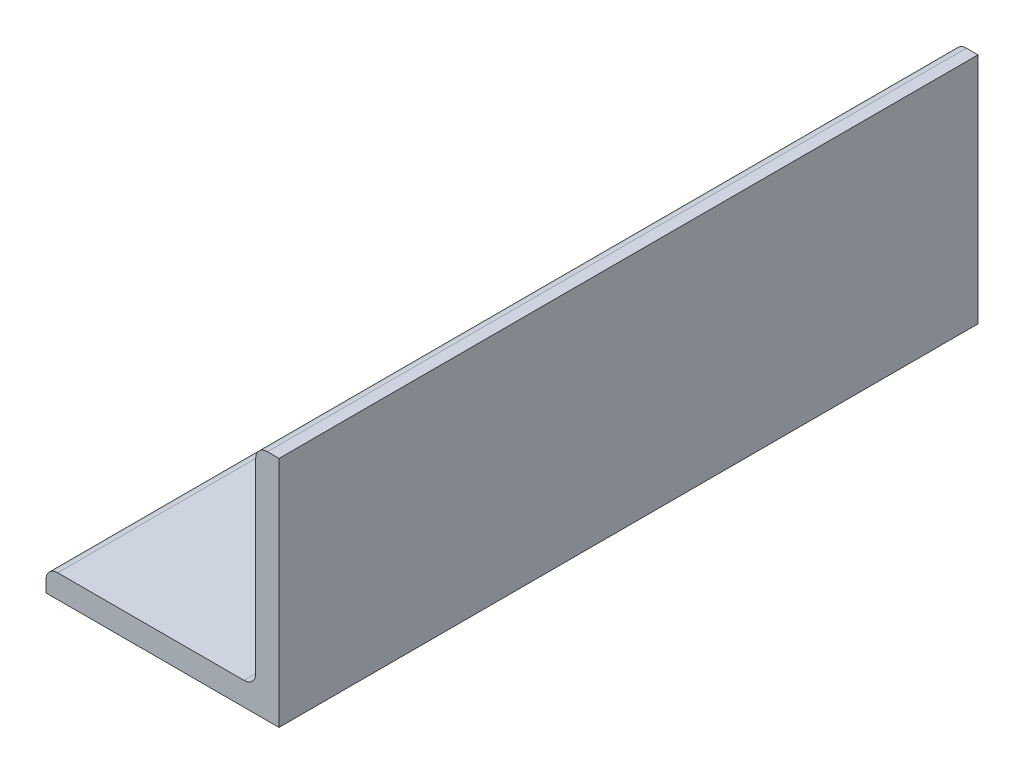
SolidWorks part; units mm, degrees
material "ASTM A36 Steel"
ref_plane "Front Plane" through (0, 0, 0) normal (0, 0, 1) x (1, 0, 0)
ref_plane "Top Plane" through (0, 0, 0) normal (0, 1, 0) x (1, 0, 0)
ref_plane "Right Plane" through (0, 0, 0) normal (1, 0, 0) x (0, 0, -1)
sketch "Sketch1" plane through (0, 0, 0) normal (0, 0, 1) x (1, 0, 0)
  line L0 (-135.6009, 27) -> (-135.6009, -3)
  line L1 (-135.6009, -3) -> (-165.6009, -3)
  line L2 (-165.6009, -3) -> (-165.6009, -1.5)
  line L3 (-164.1009, 0) -> (-140.1009, 0)
  line L4 (-138.6009, 1.5) -> (-138.6009, 25.5)
  line L5 (-137.1009, 27) -> (-135.6009, 27)
  arc A0 (-138.6009, 25.5) -> (-137.1009, 27) centre (-137.1009, 25.5) cw
  arc A1 (-140.1009, 0) -> (-138.6009, 1.5) centre (-140.1009, 1.5) ccw
  arc A2 (-165.6009, -1.5) -> (-164.1009, 0) centre (-164.1009, -1.5) cw
  point P9 (-138.6009, 27)
  point P14 (-165.6009, 0)
  dimension "D5" = 1.5
  dimension "D1" = 3
  dimension "D2" = 30
  dimension "D3" = 30
  dimension "D4" = 3
extrude "Boss-Extrude1" add sketch "Sketch1" along normal blind 90
